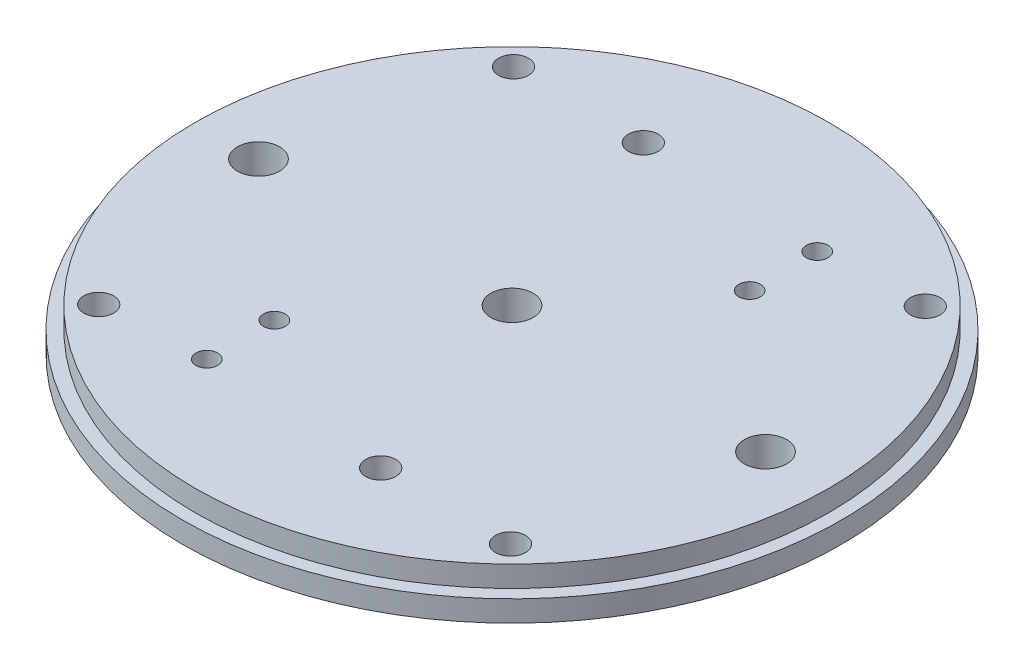
SolidWorks part; units mm, degrees
material "6061-T6 (SS)"
ref_plane "Front Plane" through (0, 0, 0) normal (0, 0, 1) x (1, 0, 0)
ref_plane "Top Plane" through (0, 0, 0) normal (0, 1, 0) x (1, 0, 0)
ref_plane "Right Plane" through (0, 0, 0) normal (1, 0, 0) x (0, 0, -1)
sketch "Sketch1" plane through (0, 0, 0) normal (0, 1, 0) x (1, 0, 0)
  circle A0 centre (0, 0) radius 49.53
  dimension "D1" = 99.06
extrude "Boss-Extrude1" add sketch "Sketch1" along normal blind 3.175
sketch "Sketch2" plane through (0, 3.175, 0) normal (0, 1, 0) x (1, 0, 0)
  circle A0 centre (0, 0) radius 47.625
  circle A1 centre (0, 0) radius 49.53 construction
  dimension "D1" = 1.905
extrude "Boss-Extrude2" add sketch "Sketch2" along normal blind 3.175
sketch "Sketch3" plane through (0, 6.35, 0) normal (0, 1, 0) x (1, 0, 0)
  line L0 (-38.1, 0) -> (38.1, 0) construction
  circle A0 centre (-38.1, 0) radius 3.175
  circle A1 centre (38.1, 0) radius 3.175
  dimension "D1" = 6.35
  dimension "D2" = 6.35
  dimension "D3" = 76.2
extrude "Cut-Extrude1" cut sketch "Sketch3" against normal through all
sketch "Sketch4" plane through (0, 6.35, 0) normal (0, 1, 0) x (1, 0, 0)
  line L0 (-34.925, 0) -> (34.925, 0) construction
  line L1 (0, 47.625) -> (0, -47.625) construction
  circle A0 centre (-38.1, 0) radius 3.175 construction
  circle A1 centre (38.1, 0) radius 3.175 construction
  circle A2 centre (0, 0) radius 47.625 construction
  circle A3 centre (0, 0) radius 47.625 construction
sketch "Sketch5" plane through (0, 6.35, 0) normal (0, 1, 0) x (1, 0, 0)
  circle A0 centre (0, 0) radius 3.175
  dimension "D1" = 6.35
extrude "Cut-Extrude2" cut sketch "Sketch5" against normal through all
hole_wizard "CSK for #8 Flat Head Machine Screw2" positions "Sketch9" profile "Sketch8" countersink size "#8" standard "ANSI Inch" end condition through all
sketch "Sketch9" plane through (0, 0, 0) normal (0, -1, 0) x (-1, 0, 0)
  circle A0 centre (31.1698, -30.9406) radius 3.9624 construction
  point P0 (31.1698, -30.9406)
sketch "Sketch8" plane through (-31.1698, 0, 30.9406) normal (1, 0, 0) x (0, 0, -1)
  line L0 (0, 0) -> (0, 6.35)
  line L1 (0, 6.35) -> (2.2479, 6.35)
  line L2 (2.2479, 6.35) -> (2.2479, 2.2645)
  line L3 (2.2479, 2.2645) -> (4.2164, 0)
  line L5 (4.2164, 0) -> (0, 0)
  line L6 (-2.2479, 2.2645) -> (-4.2164, 0) construction
  line L11 (0, -6.35) -> (0, 107.95) construction
  dimension "Thru Hole Dia." = 4.4958
  dimension "Thru Hole Depth" = 6.35
  dimension "Near C'Sink Dia." = 8.4328
  dimension "Near C'Sink Angle" = 82
pattern_circular "CirPattern1" count 4 over 360 about axis through (0, 0, 0) along (0, 1, 0) of "CSK for #8 Flat Head Machine Screw2"
hole_wizard "#8 Clearance Hole1" positions "Sketch11" profile "Sketch10" hole size "#8" standard "ANSI Inch" end condition through all
sketch "Sketch11" plane through (0, 0, 0) normal (0, -1, 0) x (-1, 0, 0)
  line L7 (-11.2935, -31.0287) -> (11.2935, 31.0287) construction
  line L8 (34.925, 0) -> (-34.925, 0) construction
  point P0 (11.2935, 31.0287)
  point P4 (-11.2935, -31.0287)
  dimension "D1" = 66.04
  dimension "D2" = 70
sketch "Sketch10" plane through (-11.2935, 0, -31.0287) normal (1, 0, 0) x (0, 0, -1)
  line L0 (0, 0) -> (0, 6.35)
  line L1 (0, 6.35) -> (2.2479, 6.35)
  line L2 (2.2479, 6.35) -> (2.2479, 0)
  line L5 (2.2479, 0) -> (0, 0)
  line L11 (0, -6.35) -> (0, 107.95) construction
  dimension "Thru Hole Dia." = 4.4958
  dimension "Thru Hole Depth" = 6.35
hole_wizard "#4 Clearance Hole1" positions "Sketch13" profile "Sketch12" hole size "#4" standard "ANSI Inch" end condition through all
sketch "Sketch13" plane through (0, 0, 0) normal (0, -1, 0) x (-1, 0, 0)
  line L0 (-15.9298, 29.9439) -> (-15.9298, 19.7839) construction
  line L2 (15.9298, -19.7839) -> (15.9298, -29.9439) construction
  line L5 (15.9298, -19.7839) -> (-15.9298, 19.7839) construction
  circle A0 centre (-31.1698, 30.9406) radius 2.2479 construction
  point P0 (-15.9298, 19.7839)
  point P2 (15.9298, -19.7839)
  point P4 (-15.9298, 29.9439)
  point P6 (15.9298, -29.9439)
  dimension "D3" = 15.24
  dimension "D1" = 10.16
  dimension "D2" = 10.16
  dimension "D5" = 25.4
sketch "Sketch12" plane through (15.9298, 0, -19.7839) normal (1, 0, 0) x (0, 0, -1)
  line L0 (0, 0) -> (0, 6.35)
  line L1 (0, 6.35) -> (1.6319, 6.35)
  line L2 (1.6319, 6.35) -> (1.6319, 0)
  line L5 (1.6319, 0) -> (0, 0)
  line L11 (0, -6.35) -> (0, 107.95) construction
  dimension "Thru Hole Dia." = 3.2639
  dimension "Thru Hole Depth" = 6.35
